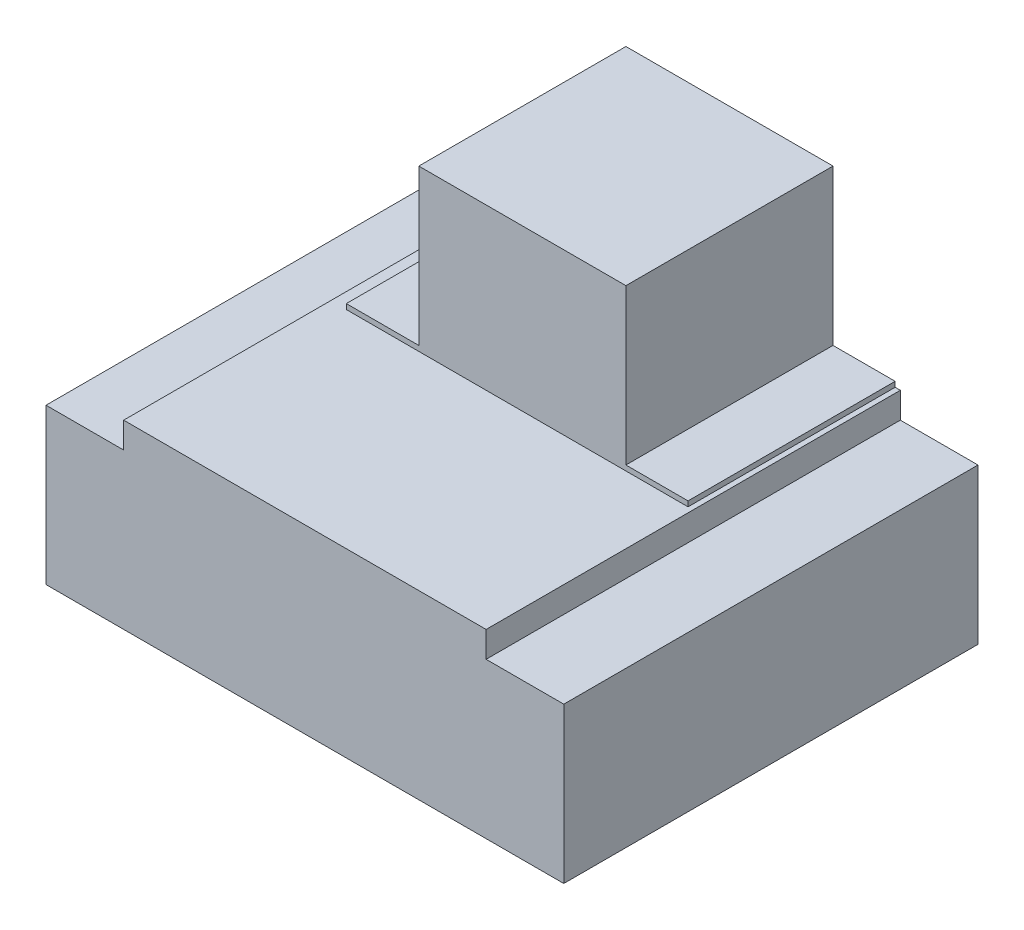
SolidWorks part; units mm, degrees
material "ABS"
ref_plane "前视基准面" through (0, 0, 0) normal (0, 0, 1) x (1, 0, 0)
ref_plane "上视基准面" through (0, 0, 0) normal (0, 1, 0) x (1, 0, 0)
ref_plane "右视基准面" through (0, 0, 0) normal (1, 0, 0) x (0, 0, -1)
sketch "草图1" plane through (0, 0, 0) normal (0, 1, 0) x (1, 0, 0)
  line L1 (0, 0) -> (100, 0)
  line L2 (0, 0) -> (0, 80)
  line L3 (0, 80) -> (100, 80)
  line L4 (100, 0) -> (100, 80)
  dimension "D1" = 100
  dimension "D2" = 80
extrude "凸台-拉伸1" add sketch "草图1" along normal blind 35
sketch "草图2" plane through (0, 35, 0) normal (0, 1, 0) x (1, 0, 0)
  line L0 (100, 80) -> (0, 80) construction
  line L1 (18, 80) -> (84, 80)
  line L2 (18, 80) -> (18, 40)
  line L3 (18, 40) -> (84, 40)
  line L4 (84, 80) -> (84, 40)
  line L5 (100, 0) -> (100, 80) construction
  line L6 (0, 80) -> (0, 0) construction
  dimension "D1" = 16
  dimension "D2" = 18
  dimension "D3" = 40
extrude "凸台-拉伸2" add sketch "草图2" along normal blind 1
sketch "草图3" plane through (0, 36, 0) normal (0, 1, 0) x (1, 0, 0)
  line L0 (84, 80) -> (18, 80) construction
  line L1 (32, 80) -> (72, 80)
  line L2 (32, 80) -> (32, 40)
  line L3 (32, 40) -> (72, 40)
  line L4 (72, 80) -> (72, 40)
  line L5 (84, 40) -> (84, 80) construction
  dimension "D1" = 40
  dimension "D2" = 40
  dimension "D3" = 12
extrude "凸台-拉伸3" add sketch "草图3" along normal blind 30
sketch "草图4" plane through (0, 35, 0) normal (0, 1, 0) x (1, 0, 0)
  line L0 (0, 0) -> (100, 0) construction
  line L1 (0, 80) -> (15, 80)
  line L2 (0, 80) -> (0, 0)
  line L3 (0, 0) -> (15, 0)
  line L4 (15, 80) -> (15, 0)
  line L6 (100, 80) -> (85, 80)
  line L7 (100, 80) -> (100, 0)
  line L8 (100, 0) -> (85, 0)
  line L9 (85, 80) -> (85, 0)
  dimension "D1" = 15
  dimension "D2" = 15
extrude "切除-拉伸1" cut sketch "草图4" against normal blind 5
